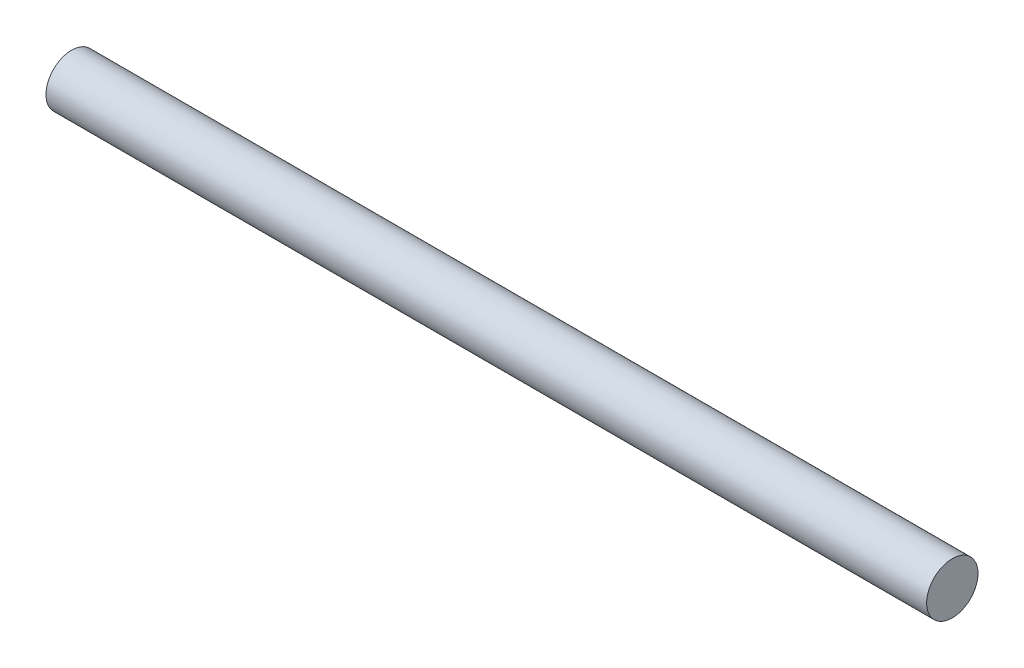
SolidWorks part; units mm, degrees
ref_plane "Front Plane" through (0, 0, 0) normal (0, 0, 1) x (1, 0, 0)
ref_plane "Top Plane" through (0, 0, 0) normal (0, 1, 0) x (1, 0, 0)
ref_plane "Right Plane" through (0, 0, 0) normal (1, 0, 0) x (0, 0, -1)
sketch "Sketch1" plane through (0, 0, 0) normal (1, 0, 0) x (0, 0, -1)
  circle A0 centre (0, 0) radius 1.4
extrude "Extrude1" add sketch "Sketch1" along normal blind 48
